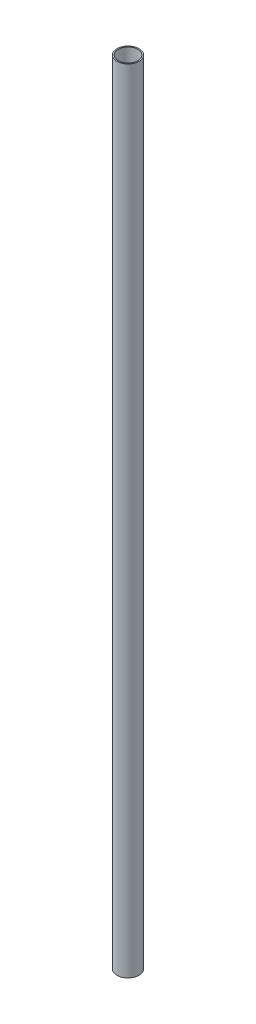
SolidWorks part; units mm, degrees
ref_plane "Front Plane" through (0, 0, 0) normal (0, 0, 1) x (1, 0, 0)
ref_plane "Top Plane" through (0, 0, 0) normal (0, 1, 0) x (1, 0, 0)
ref_plane "Right Plane" through (0, 0, 0) normal (1, 0, 0) x (0, 0, -1)
sketch "Sketch1" plane through (0, 0, 0) normal (0, 1, 0) x (1, 0, 0)
  circle A0 centre (0, 0) radius 11.665
  circle A1 centre (0, 0) radius 10.395
  dimension "D1" = 23.33
  dimension "D2" = 1.27
extrude "Boss-Extrude1" add sketch "Sketch1" along normal mid plane 838.2
